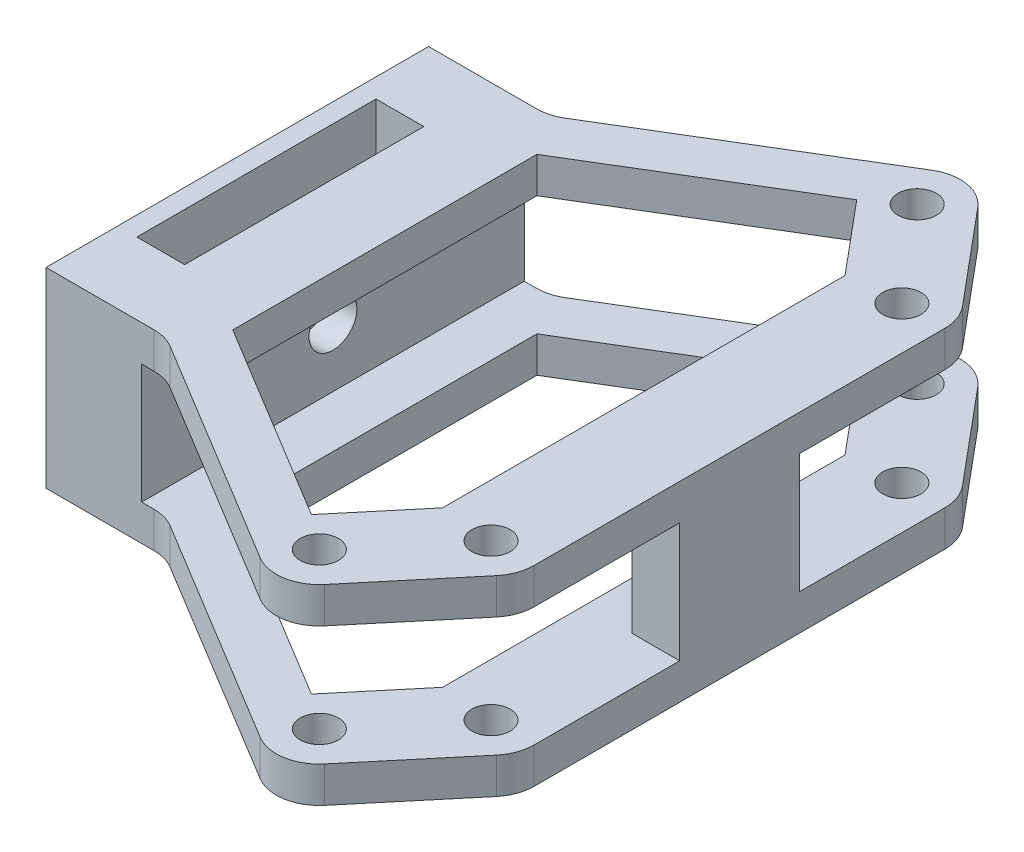
SolidWorks part; units mm, degrees
ref_plane "Front Plane" through (0, 0, 0) normal (0, 0, 1) x (1, 0, 0)
ref_plane "Top Plane" through (0, 0, 0) normal (0, 1, 0) x (1, 0, 0)
ref_plane "Right Plane" through (0, 0, 0) normal (1, 0, 0) x (0, 0, -1)
sketch "Sketch1" plane through (0, 0, 0) normal (0, 1, 0) x (1, 0, 0)
  line L0 (74.9899, 70.1996) -> (27.241, 41.3004)
  line L1 (0, 40) -> (22.581, 40)
  line L2 (0, 40) -> (0, -40)
  line L3 (0, -40) -> (22.581, -40)
  line L5 (25, 40.3312) -> (25, -40.3312)
  line L7 (86.5538, 68.2738) -> (102.9038, 48.7238)
  line L8 (105, 42.95) -> (105, -42.95)
  line L9 (-20.5983, 0) -> (217.4684, 0) construction
  line L10 (74.9899, -70.1996) -> (27.241, -41.3004)
  line L11 (86.5538, -68.2738) -> (102.9038, -48.7238)
  line L12 (30.85, -31.7958) -> (30.85, 31.7958)
  line L13 (30.85, 31.7958) -> (72.5093, 57.0093)
  line L14 (72.5093, 57.0093) -> (85, 42.074)
  line L15 (85, 42.074) -> (85, -42.074)
  line L16 (72.5093, -57.0093) -> (85, -42.074)
  line L17 (30.85, -31.7958) -> (72.5093, -57.0093)
  line L19 (4, -25) -> (14, -25)
  line L20 (4, -25) -> (4, 25)
  line L21 (4, 25) -> (14, 25)
  line L22 (14, -25) -> (14, 25)
  arc A1 (102.9038, 48.7238) -> (105, 42.95) centre (96, 42.95) cw
  arc A2 (86.5538, 68.2738) -> (74.9899, 70.1996) centre (79.65, 62.5) ccw
  arc A3 (86.5538, -68.2738) -> (74.9899, -70.1996) centre (79.65, -62.5) cw
  arc A4 (102.9038, -48.7238) -> (105, -42.95) centre (96, -42.95) ccw
  circle A5 centre (79.65, 62.5) radius 4
  circle A6 centre (96, 42.95) radius 4
  circle A7 centre (96, -42.95) radius 4
  circle A8 centre (79.65, -62.5) radius 4
  arc A9 (22.581, 40) -> (27.241, 41.3004) centre (22.581, 49) ccw
  arc A10 (22.581, -40) -> (27.241, -41.3004) centre (22.581, -49) cw
  point P0 (0, 0)
  point P1 (25, -40.3312)
  point P4 (25, 40.3312)
  point P22 (105, 0)
  point P24 (0, 0)
  point P27 (94.7288, 58.4988)
  point P35 (85, 0)
  point P36 (30.85, 0)
  point P46 (0, 0)
  dimension "D5" = 8
  dimension "D8" = 9
  dimension "D9" = 9
  dimension "D17" = 9
  dimension "D18" = 9
  dimension "D19" = 25
  dimension "D1" = 80
  dimension "D2" = 25
  dimension "D3" = 105
  dimension "D4" = 85.9
  dimension "D6" = 16.35
  dimension "D7" = 19.55
  dimension "D10" = 20
  dimension "D11" = 54.15
  dimension "D12" = 10
  dimension "D13" = 18
  dimension "D14" = 4
  dimension "D15" = 50
  dimension "D16" = 10
extrude "Boss-Extrude2" add sketch "Sketch1" against normal mid plane 40 contours A10 L3 L2 L1 A9 L0 A2 L7 A1 L8 A4 L11 A3 L10 | A7 | A8 | A6 | A5 | L16 L15 L14 L13 L12 L17 | L20 L19 L22 L21
sketch "Sketch4" plane through (0, 0, 0) normal (0, 0, 1) x (1, 0, 0)
  line L1 (105, -12.5) -> (20, -12.5)
  line L2 (105, -12.5) -> (105, 12.5)
  line L3 (105, 12.5) -> (20, 12.5)
  line L4 (20, -12.5) -> (20, 12.5)
  line L5 (105, -12.5) -> (20, 12.5) construction
  line L6 (105, 12.5) -> (20, -12.5) construction
  line L7 (0, 0) -> (120.5161, 0) construction
  line L8 (105, -20) -> (105, 20) construction
  point P0 (62.5, 0)
  dimension "D1" = 25
  dimension "D2" = 85
extrude "Cut-Extrude1" cut sketch "Sketch4" against normal through all both and the other way through all
sketch "Sketch5" plane through (105, 0, 0) normal (1, 0, 0) x (0, 0, -1)
  line L0 (40, 12.5) -> (-40, 12.5) construction
  line L1 (-12.5, -12.5) -> (12.5, -12.5)
  line L2 (-12.5, -12.5) -> (-12.5, 12.5)
  line L3 (-12.5, 12.5) -> (12.5, 12.5)
  line L4 (12.5, -12.5) -> (12.5, 12.5)
  line L5 (-12.5, -12.5) -> (12.5, 12.5) construction
  line L6 (-12.5, 12.5) -> (12.5, -12.5) construction
  point P0 (0, 0)
  dimension "D1" = 25
extrude "Boss-Extrude4" add sketch "Sketch5" against normal blind 10
hole_wizard "Hole1" positions "Sketch6" profile "Sketch7" legacy
sketch "Sketch6" plane through (0, 0, 0) normal (-1, 0, 0) x (0, 0, 1)
  point P0 (0, 0)
sketch "Sketch7" plane through (0, 0, 0) normal (0, 1, 0) x (0, 0, 1)
  line L0 (0, 0) -> (0, 20)
  line L1 (0, 20) -> (5, 20)
  line L2 (5, 20) -> (5, 3)
  line L3 (5, 3) -> (12, 3)
  line L4 (12, 3) -> (12, 0)
  line L5 (12, 0) -> (0, 0)
  line L6 (0, 110) -> (0, -10) construction
  dimension "Diameter" = 10
  dimension "Depth" = 20
  dimension "C-Bore Diameter" = 24
  dimension "C-Bore Depth" = 3
